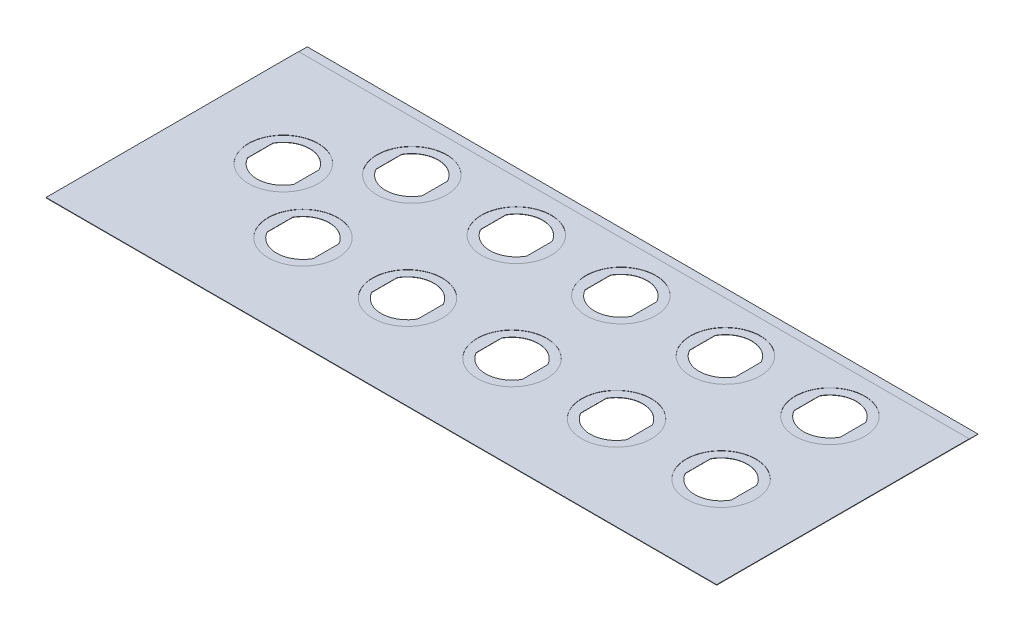
SolidWorks part; units mm, degrees
ref_plane "Front Plane" through (0, 0, 0) normal (0, 0, 1) x (1, 0, 0)
ref_plane "Top Plane" through (0, 0, 0) normal (0, 1, 0) x (1, 0, 0)
ref_plane "Right Plane" through (0, 0, 0) normal (1, 0, 0) x (0, 0, -1)
sketch "Sketch1" plane through (0, 0, 0) normal (0, 1, 0) x (1, 0, 0)
  line L1 (-77, 30) -> (77, 30)
  line L2 (-77, 30) -> (-77, -30)
  line L3 (-77, -30) -> (77, -30)
  line L4 (77, 30) -> (77, -30)
  line L5 (-77, 30) -> (77, -30) construction
  line L6 (-77, -30) -> (77, 30) construction
  point P0 (0, 0)
  dimension "D1" = 154
  dimension "D2" = 60
extrude "Boss-Extrude1" add sketch "Sketch1" along normal blind 0.1
sketch "Sketch2" plane through (0, 0.1, 0) normal (0, 1, 0) x (1, 0, 0)
  line L0 (51.2, 19.4176) -> (51.2, 13.5824)
  line L1 (61.8, 19.4176) -> (61.8, 13.5824)
  line L3 (-65.275, 37.7995) -> (-65.275, -44.9406) construction
  line L4 (65.275, 37.7995) -> (65.275, -50.8521) construction
  line L5 (37.8, 19.4176) -> (37.8, 13.5824)
  line L6 (27.2, 19.4176) -> (27.2, 13.5824)
  line L7 (13.8, 19.4176) -> (13.8, 13.5824)
  line L8 (3.2, 19.4176) -> (3.2, 13.5824)
  line L9 (-10.2, 19.4176) -> (-10.2, 13.5824)
  line L10 (-20.8, 19.4176) -> (-20.8, 13.5824)
  line L11 (-34.2, 19.4176) -> (-34.2, 13.5824)
  line L12 (-44.8, 19.4176) -> (-44.8, 13.5824)
  line L13 (37.8, -5.5824) -> (37.8, -11.4176)
  line L14 (27.2, -5.5824) -> (27.2, -11.4176)
  line L15 (13.8, -5.5824) -> (13.8, -11.4176)
  line L16 (3.2, -5.5824) -> (3.2, -11.4176)
  line L17 (-10.2, -5.5824) -> (-10.2, -11.4176)
  line L18 (-20.8, -5.5824) -> (-20.8, -11.4176)
  line L19 (-34.2, -5.5824) -> (-34.2, -11.4176)
  line L20 (-44.8, -5.5824) -> (-44.8, -11.4176)
  line L21 (61.8, -5.5824) -> (61.8, -11.4176)
  line L22 (51.2, -5.5824) -> (51.2, -11.4176)
  line L23 (-51.2, 6.9176) -> (-51.2, 1.0824)
  line L24 (-61.8, 6.9176) -> (-61.8, 1.0824)
  arc A0 (61.8, 19.4176) -> (51.2, 19.4176) centre (56.5, 16.5) ccw
  arc A1 (51.2, 13.5824) -> (61.8, 13.5824) centre (56.5, 16.5) ccw
  circle A2 centre (56.5, 16.5) radius 8 construction
  circle A3 centre (32.5, 16.5) radius 8 construction
  arc A4 (37.8, 19.4176) -> (27.2, 19.4176) centre (32.5, 16.5) ccw
  arc A5 (27.2, 13.5824) -> (37.8, 13.5824) centre (32.5, 16.5) ccw
  circle A6 centre (8.5, 16.5) radius 8 construction
  arc A7 (13.8, 19.4176) -> (3.2, 19.4176) centre (8.5, 16.5) ccw
  arc A8 (3.2, 13.5824) -> (13.8, 13.5824) centre (8.5, 16.5) ccw
  circle A9 centre (-15.5, 16.5) radius 8 construction
  arc A10 (-10.2, 19.4176) -> (-20.8, 19.4176) centre (-15.5, 16.5) ccw
  arc A11 (-20.8, 13.5824) -> (-10.2, 13.5824) centre (-15.5, 16.5) ccw
  circle A12 centre (-39.5, 16.5) radius 8 construction
  arc A13 (-34.2, 19.4176) -> (-44.8, 19.4176) centre (-39.5, 16.5) ccw
  arc A14 (-44.8, 13.5824) -> (-34.2, 13.5824) centre (-39.5, 16.5) ccw
  circle A15 centre (32.5, -8.5) radius 8 construction
  arc A16 (37.8, -5.5824) -> (27.2, -5.5824) centre (32.5, -8.5) ccw
  arc A17 (27.2, -11.4176) -> (37.8, -11.4176) centre (32.5, -8.5) ccw
  circle A18 centre (8.5, -8.5) radius 8 construction
  arc A19 (13.8, -5.5824) -> (3.2, -5.5824) centre (8.5, -8.5) ccw
  arc A20 (3.2, -11.4176) -> (13.8, -11.4176) centre (8.5, -8.5) ccw
  circle A21 centre (-15.5, -8.5) radius 8 construction
  arc A22 (-10.2, -5.5824) -> (-20.8, -5.5824) centre (-15.5, -8.5) ccw
  arc A23 (-20.8, -11.4176) -> (-10.2, -11.4176) centre (-15.5, -8.5) ccw
  circle A24 centre (-39.5, -8.5) radius 8 construction
  arc A25 (-34.2, -5.5824) -> (-44.8, -5.5824) centre (-39.5, -8.5) ccw
  arc A26 (-44.8, -11.4176) -> (-34.2, -11.4176) centre (-39.5, -8.5) ccw
  circle A27 centre (56.5, -8.5) radius 8 construction
  arc A28 (61.8, -5.5824) -> (51.2, -5.5824) centre (56.5, -8.5) ccw
  arc A29 (51.2, -11.4176) -> (61.8, -11.4176) centre (56.5, -8.5) ccw
  arc A30 (-61.8, 1.0824) -> (-51.2, 1.0824) centre (-56.5, 4) ccw
  circle A31 centre (-56.5, 4) radius 8 construction
  arc A32 (-51.2, 6.9176) -> (-61.8, 6.9176) centre (-56.5, 4) ccw
  dimension "D1" = 12.1
  dimension "D4" = 16
  dimension "D10" = 16
  dimension "D11" = 6.05
  dimension "D12" = 10.6
  dimension "D2" = 10.6
  dimension "D3" = 5.3
  dimension "D5" = 16.5
  dimension "D6" = 130.55
  dimension "D7" = 65.275
  dimension "D13" = 5.3
  dimension "D14" = 56.5
  dimension "D15" = 56.5
  dimension "D16" = 12.5
  dimension "D8" = 5
  dimension "D9" = 2
extrude "Cut-Extrude1" cut sketch "Sketch2" against normal through all
sketch "Sketch3" plane through (0, 0.1, 0) normal (0, 1, 0) x (1, 0, 0)
  line L0 (-77, 30) -> (-77, -30) construction
  line L1 (77, 30) -> (-77, 30)
  line L2 (77, 30) -> (77, 28)
  line L3 (77, 28) -> (-77, 28)
  line L4 (-77, 30) -> (-77, 28)
  circle A0 centre (-56.5, 4) radius 8
  circle A1 centre (56.5, 16.5) radius 8
  circle A2 centre (32.5, 16.5) radius 8
  circle A3 centre (8.5, 16.5) radius 8
  circle A4 centre (-15.5, 16.5) radius 8
  circle A5 centre (-39.5, 16.5) radius 8
  circle A6 centre (32.5, -8.5) radius 8
  circle A7 centre (8.5, -8.5) radius 8
  circle A8 centre (-15.5, -8.5) radius 8
  circle A9 centre (-39.5, -8.5) radius 8
  circle A10 centre (56.5, -8.5) radius 8
  dimension "D1" = 16
  dimension "D2" = 16
  dimension "D5" = 2
  dimension "D3" = 5
  dimension "D4" = 2
extrude "Cut-Extrude2" cut sketch "Sketch3" against normal blind 0.05
